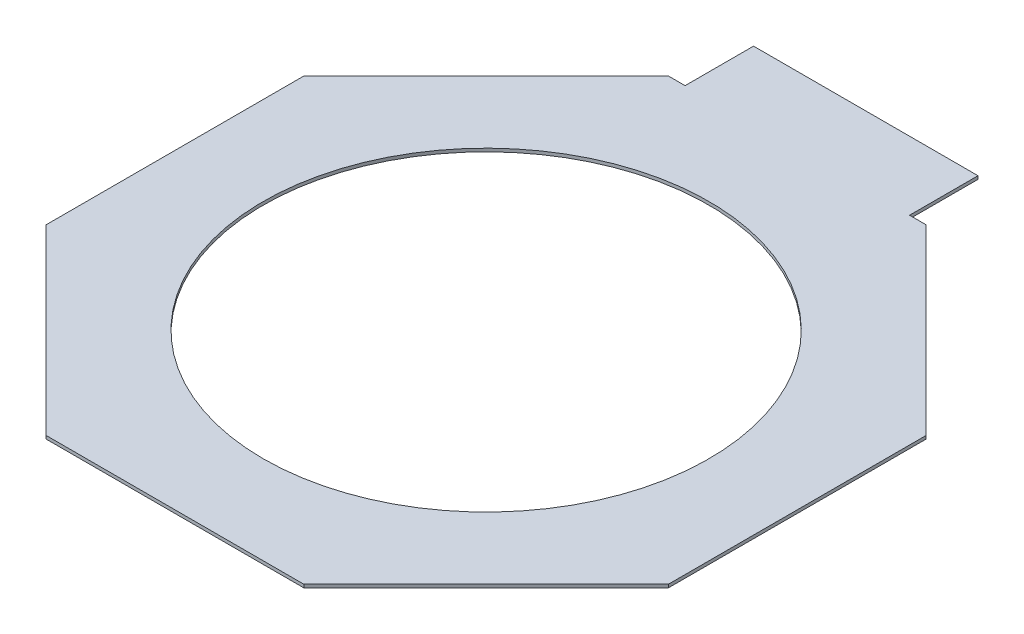
SolidWorks part; units mm, degrees
material "Náilon 101"
ref_plane "Plano frontal" through (0, 0, 0) normal (0, 0, 1) x (1, 0, 0)
ref_plane "Plano superior" through (0, 0, 0) normal (0, 1, 0) x (1, 0, 0)
ref_plane "Plano direito" through (0, 0, 0) normal (1, 0, 0) x (0, 0, -1)
sketch "Esboço1" plane through (0, 0, 0) normal (0, 1, 0) x (1, 0, 0)
  line L0 (-7.05, 19.55) -> (-8.0979, 19.55)
  line L1 (8.0979, 19.55) -> (7.05, 19.55)
  line L2 (-8.0979, 19.55) -> (-19.55, 8.0979)
  line L3 (-19.55, 8.0979) -> (-19.55, -8.0979)
  line L4 (-19.55, -8.0979) -> (-8.0979, -19.55)
  line L5 (-8.0979, -19.55) -> (8.0979, -19.55)
  line L6 (8.0979, -19.55) -> (19.55, -8.0979)
  line L7 (19.55, -8.0979) -> (19.55, 8.0979)
  line L8 (19.55, 8.0979) -> (8.0979, 19.55)
  line L10 (-7.05, 19.55) -> (-7.05, 23.85)
  line L11 (-7.05, 23.85) -> (7.05, 23.85)
  line L12 (7.05, 19.55) -> (7.05, 23.85)
  circle A0 centre (0, 0) radius 14
  arc A1 (-13.8239, 13.8239) -> (13.8239, 13.8239) centre (0, 0) ccw construction
  point P3 (0, 19.55)
  point P19 (0, 23.85)
  dimension "D1" = 28
  dimension "D2" = 39.1
  dimension "D3" = 14.1
  dimension "D4" = 4.3
extrude "Ressalto-extrusão1" add sketch "Esboço1" along normal mid plane 0.2
